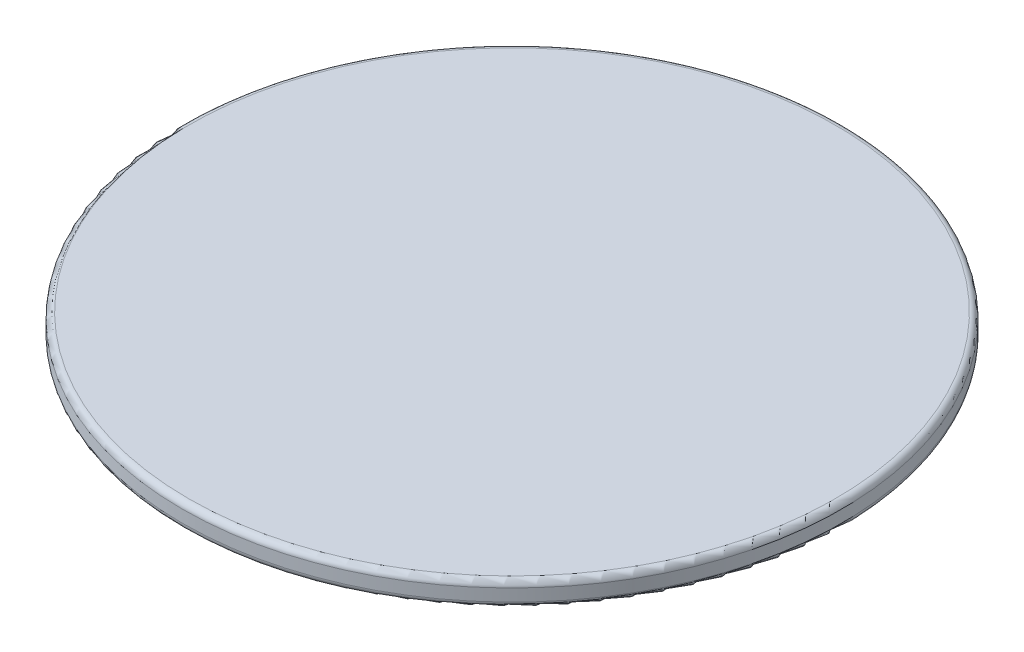
SolidWorks part; units mm, degrees
ref_plane "Front Plane" through (0, 0, 0) normal (0, 0, 1) x (1, 0, 0)
ref_plane "Top Plane" through (0, 0, 0) normal (0, 1, 0) x (1, 0, 0)
ref_plane "Right Plane" through (0, 0, 0) normal (1, 0, 0) x (0, 0, -1)
sketch "Sketch1" plane through (0, 0, 0) normal (0, 1, 0) x (1, 0, 0)
  circle A0 centre (0, 0) radius 13.5
  dimension "D1" = 27
extrude "Boss-Extrude1" add sketch "Sketch1" along normal blind 1
fillet "Fillet1" radius 0.25 2 edges at (0, 0, 13.5) (0, 1, 13.5)
